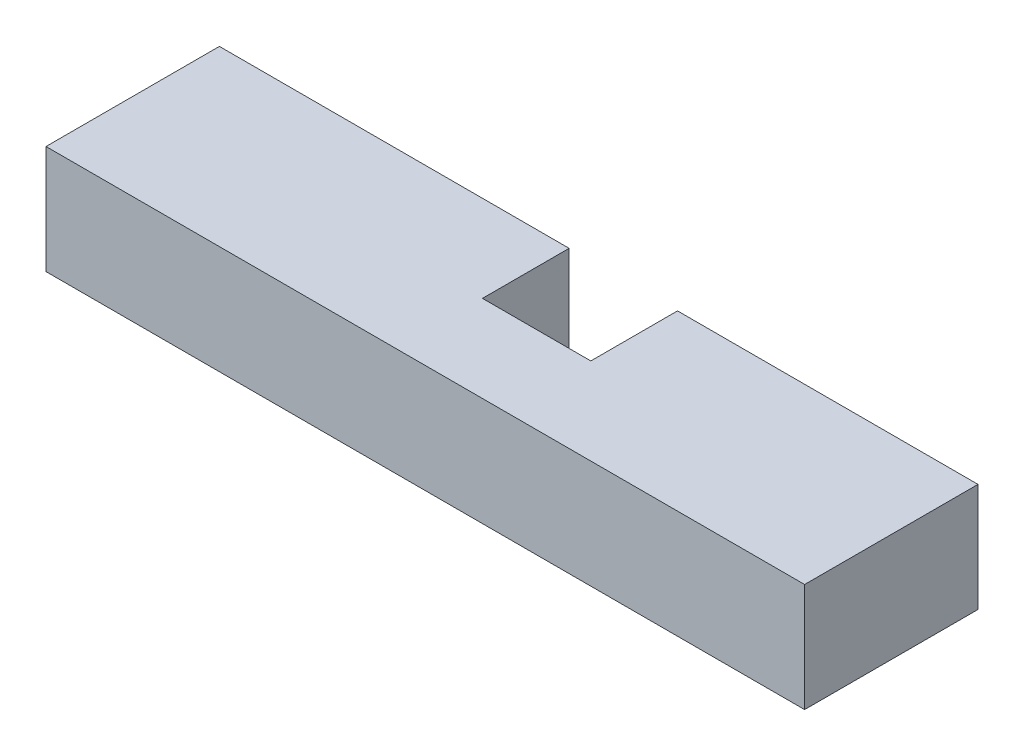
SolidWorks part; units mm, degrees
ref_plane "Front Plane" through (0, 0, 0) normal (0, 0, 1) x (1, 0, 0)
ref_plane "Top Plane" through (0, 0, 0) normal (0, 1, 0) x (1, 0, 0)
ref_plane "Right Plane" through (0, 0, 0) normal (1, 0, 0) x (0, 0, -1)
sketch "Elevator Paddle Support Strut" plane through (0, 0, 0) normal (0, 1, 0) x (1, 0, 0)
  line L0 (0, -5.08) -> (0, 0) construction
  line L1 (-22.225, -5.08) -> (22.225, -5.08)
  line L2 (-22.225, -5.08) -> (-22.225, 5.08)
  line L3 (-22.225, 5.08) -> (-1.7321, 5.08)
  line L4 (22.225, -5.08) -> (22.225, 5.08)
  line L5 (-22.225, -5.08) -> (0, 0) construction
  line L6 (-22.225, 5.08) -> (-1.7321, 0.3959) construction
  line L7 (-22.225, 0) -> (22.225, 0) construction
  line L8 (-1.7321, 0) -> (4.6179, 0)
  line L9 (-1.7321, 0) -> (-1.7321, 5.08)
  line L10 (4.6179, 1.0555) -> (22.225, 5.08) construction
  line L11 (4.6179, 0) -> (4.6179, 5.08)
  line L13 (0, 0) -> (22.225, -5.08) construction
  line L14 (4.6179, 5.08) -> (22.225, 5.08)
  point P0 (0, 0)
  dimension "D1" = 10.16
  dimension "D2" = 44.45
  dimension "D3" = 6.35
extrude "Boss-Extrude1" add sketch "Elevator Paddle Support Strut" along normal blind 6.35 contours L11 L8 L9 L3 L2 L1 L4
equation "\"Ball Diameter\"= 1.75in"
equation "\"Sheet Thickness\"= 0.25in"
equation "\"Screw Diameter\"= .17in"
equation "\"Robot Diameter\"= 16in"
equation "\"Castor Screw Diameter\"= 0.22in"
equation "\"Wheel Diameter\" = 4in"
equation "\"Nut Diameter\" = 8.4mm"
equation "\"Nut Height\" = 2.9mm"
equation "\"Screw Height\" = 0.55in"
equation "\"D2@Elevator Paddle Support Strut\"=\"Ball Diameter\""
equation "\"D3@Elevator Paddle Support Strut\"=\"Sheet Thickness\""
equation "\"D1@Boss-Extrude1\"=\"Sheet Thickness\""
